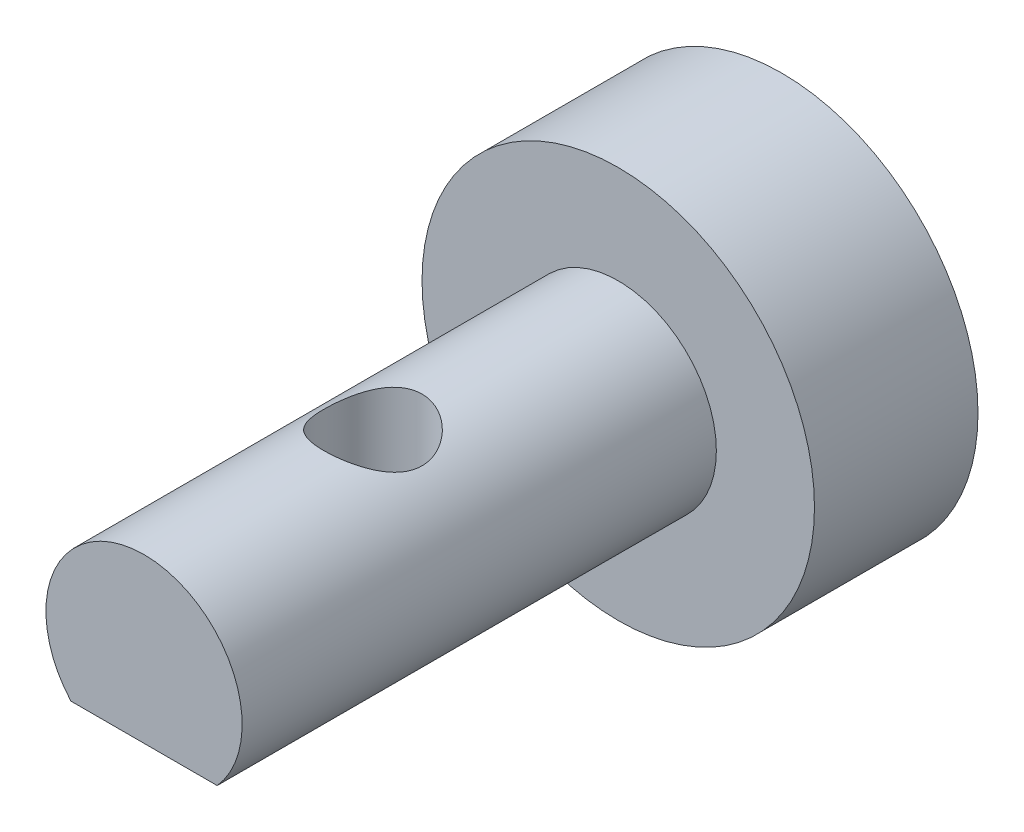
SolidWorks part; units mm, degrees
ref_plane "Front Plane" through (0, 0, 0) normal (0, 0, 1) x (1, 0, 0)
ref_plane "Top Plane" through (0, 0, 0) normal (0, 1, 0) x (1, 0, 0)
ref_plane "Right Plane" through (0, 0, 0) normal (1, 0, 0) x (0, 0, -1)
sketch "Sketch1" plane through (0, 0, 0) normal (0, 0, 1) x (1, 0, 0)
  circle A1 centre (0, 0) radius 6
  dimension "D1" = 12
extrude "Boss-Extrude1" add sketch "Sketch1" along normal blind 5
sketch "Sketch2" plane through (0, 0, 5) normal (0, 0, 1) x (1, 0, 0)
  line L0 (0, -1) -> (0, 1) construction
  circle A2 centre (0, 0) radius 3
  dimension "D1" = 6
extrude "Boss-Extrude2" add sketch "Sketch2" along normal blind 2.5
sketch "Sketch3" plane through (0, 0, 7.5) normal (0, 0, 1) x (1, 0, 0)
  line L0 (-2.2361, -2) -> (2.2361, -2)
  line L2 (0, 3) -> (0, -2) construction
  circle A0 centre (0, 0) radius 3 construction
  arc A1 (2.2361, -2) -> (-2.2361, -2) centre (0, 0) ccw
  dimension "D1" = 5
extrude "Boss-Extrude3" add sketch "Sketch3" along normal blind 12
sketch "Sketch4" plane through (0, -2, 0) normal (0, -1, 0) x (1, 0, 0)
  line L0 (0, 19.5) -> (0, 7.5) construction
  line L1 (-2.2361, 19.5) -> (2.2361, 19.5) construction
  line L2 (-2.2361, 7.5) -> (2.2361, 7.5) construction
  circle A0 centre (0, 12.5) radius 1.5
  dimension "D1" = 3
  dimension "D2" = 7
extrude "Cut-Extrude1" cut sketch "Sketch4" against normal up to next
